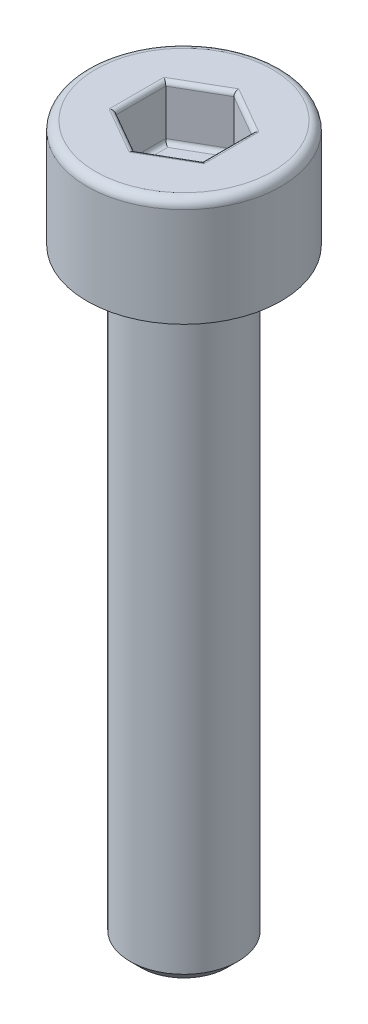
SolidWorks part; units mm, degrees
ref_plane "Front Plane" through (0, 0, 0) normal (0, 0, 1) x (1, 0, 0)
ref_plane "Top Plane" through (0, 0, 0) normal (0, 1, 0) x (1, 0, 0)
ref_plane "Right Plane" through (0, 0, 0) normal (1, 0, 0) x (0, 0, -1)
sketch "Sketch1" plane through (0, 0, 0) normal (0, 0, 1) x (1, 0, 0)
  line L0 (0, 0) -> (0, -47.0967) construction
  line L1 (0, -16.5) -> (-1.25, -16.5)
  line L2 (-1.25, -16.5) -> (-1.25, -2.5)
  line L3 (-1.25, -2.5) -> (-2.25, -2.5)
  line L4 (-2.25, -2.5) -> (-2.25, 0)
  line L5 (-2.25, 0) -> (0, 0)
  line L6 (0, 0) -> (0, -16.5)
  point P3 (-0.625, -16.5)
  dimension "D1" = 14
  dimension "d" = 2.5
  dimension "k" = 2.5
  dimension "dk" = 4.5
revolve "Revolve1" add sketch "Sketch1" angle 360 about L0
chamfer "Chamfer1" distance 0.25 angle 45 2 edges at (0, -2.5, 1.25) (0, -16.5, 1.25)
fillet "Fillet1" radius 0.2 1 edges at (0, 0, 2.25)
sketch "Sketch2" plane through (0, 0, 0) normal (0, 1, 0) x (1, 0, 0)
  line L1 (0, 1.1547) -> (-1, 0.5774)
  line L2 (-1, 0.5774) -> (-1, -0.5774)
  line L3 (-1, -0.5774) -> (0, -1.1547)
  line L4 (0, -1.1547) -> (1, -0.5774)
  line L5 (1, -0.5774) -> (1, 0.5774)
  line L6 (1, 0.5774) -> (0, 1.1547)
  circle A0 centre (0, 0) radius 1 construction
  dimension "s" = 2
extrude "Cut-Extrude1" cut sketch "Sketch2" against normal blind 1.25
fillet "Fillet2" radius 0.1 12 edges at (-0.5, 0, -0.866) (-1, 0, 0) (-0.5, 0, 0.866) (0.5, 0, 0.866) (1, 0, 0) (0.5, 0, -0.866) (1, -1.25, 0) (0.5, -1.25, 0.866) (-0.5, -1.25, 0.866) (-1, -1.25, 0) (-0.5, -1.25, -0.866) (0.5, -1.25, -0.866)
